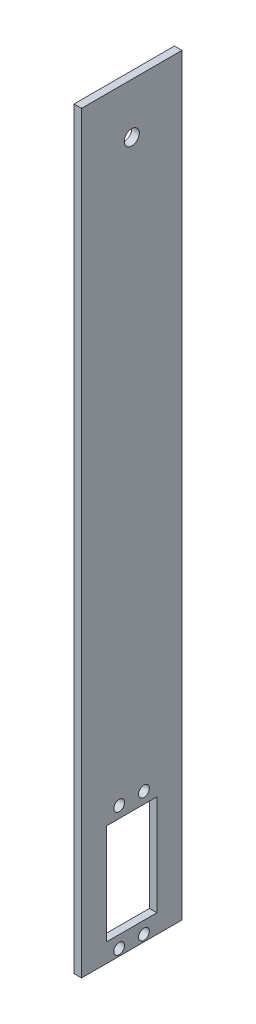
SolidWorks part; units mm, degrees
ref_plane "Front Plane" through (0, 0, 0) normal (0, 0, 1) x (1, 0, 0)
ref_plane "Top Plane" through (0, 0, 0) normal (0, 1, 0) x (1, 0, 0)
ref_plane "Right Plane" through (0, 0, 0) normal (1, 0, 0) x (0, 0, -1)
sketch "Sketch1" plane through (0, 0, 0) normal (1, 0, 0) x (0, 0, -1)
  line L1 (-20, -150) -> (20, -150)
  line L2 (-20, -150) -> (-20, 150)
  line L3 (-20, 150) -> (20, 150)
  line L4 (20, -150) -> (20, 150)
  line L5 (0, 150) -> (0, -150) construction
  line L6 (-20, 0) -> (20, 0) construction
  point P0 (0, 0)
  dimension "D1" = 300
  dimension "D2" = 40
extrude "Boss-Extrude1" add sketch "Sketch1" along normal blind 3
sketch "Sketch2" plane through (3, 0, 0) normal (1, 0, 0) x (0, 0, -1)
  line L0 (-20, 130) -> (20, 130) construction
  line L1 (-20, 150) -> (-20, -150) construction
  line L2 (20, -150) -> (20, 150) construction
  line L3 (20, 150) -> (-20, 150) construction
  circle A0 centre (0, 130) radius 3
  dimension "D1" = 20
extrude "Cut-Extrude1" cut sketch "Sketch2" against normal blind 3
sketch "Sketch3" plane through (3, 0, 0) normal (1, 0, 0) x (0, 0, -1)
  line L0 (-20, -95) -> (20, -95) construction
  line L1 (-20, 150) -> (-20, -150) construction
  line L2 (20, -150) -> (20, 150) construction
  line L3 (-20, -150) -> (20, -150) construction
  line L4 (0, -95) -> (0, -150) construction
  line L6 (-10, -142.5) -> (10, -142.5)
  line L7 (-10, -142.5) -> (-10, -102.5)
  line L8 (-10, -102.5) -> (10, -102.5)
  line L9 (10, -142.5) -> (10, -102.5)
  line L10 (0, -102.5) -> (0, -142.5) construction
  line L11 (-10, -122.5) -> (10, -122.5) construction
  circle A0 centre (-5.025, -147.31) radius 2.15
  circle A1 centre (4.845, -147.31) radius 2.15
  circle A2 centre (-5.025, -98.01) radius 2.15
  circle A3 centre (4.845, -98.01) radius 2.15
  point P10 (0, -122.5)
  dimension "D1" = 55
  dimension "D2" = 40
  dimension "D3" = 20
extrude "Cut-Extrude2" cut sketch "Sketch3" against normal blind 3
